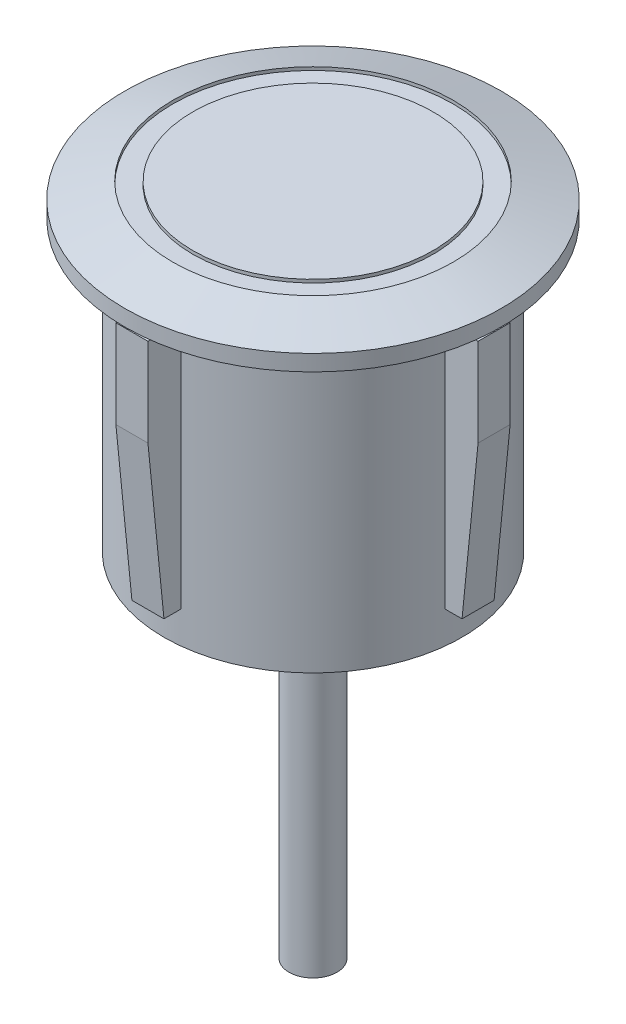
SolidWorks part; units mm, degrees
ref_plane "前视基准面" through (0, 0, 0) normal (0, 0, 1) x (1, 0, 0)
ref_plane "上视基准面" through (0, 0, 0) normal (0, 1, 0) x (1, 0, 0)
ref_plane "右视基准面" through (0, 0, 0) normal (1, 0, 0) x (0, 0, -1)
sketch "草图1" plane through (0, 0, 0) normal (0, 1, 0) x (1, 0, 0)
  circle A0 centre (0, 0) radius 9.3
  dimension "D1" = 18.6
extrude "凸台-拉伸1" add sketch "草图1" along normal blind 20
sketch "草图2" plane through (0, 20, 0) normal (0, 1, 0) x (1, 0, 0)
  circle A0 centre (0, 0) radius 11.75
  dimension "D1" = 23.5
extrude "凸台-拉伸2" add sketch "草图2" against normal blind 2
chamfer "倒角1" distance 1 distance2 3 1 edges at (0, 20, 11.75)
sketch "草图3" plane through (0, 0, 0) normal (0, -1, 0) x (1, 0, 0)
  circle A0 centre (0, 0) radius 1.5
  dimension "D1" = 3
extrude "凸台-拉伸3" add sketch "草图3" along normal blind 22
sketch "草图4" plane through (0, 0, 0) normal (0, -1, 0) x (1, 0, 0)
  line L0 (0, 0) -> (6.8393, 0) construction
  line L1 (1, 7.3) -> (-1, 7.3)
  line L2 (1, 7.3) -> (1, 11.3)
  line L3 (1, 11.3) -> (-1, 11.3)
  line L4 (-1, 7.3) -> (-1, 11.3)
  line L5 (1, 7.3) -> (-1, 11.3) construction
  line L6 (1, 11.3) -> (-1, 7.3) construction
  line L7 (1, -11.3) -> (-1, -7.3) construction
  line L8 (1, -7.3) -> (-1, -11.3) construction
  line L9 (-1, -7.3) -> (-1, -11.3)
  line L10 (1, -11.3) -> (-1, -11.3)
  line L11 (1, -7.3) -> (1, -11.3)
  line L12 (1, -7.3) -> (-1, -7.3)
  line L13 (0, 0) -> (0, 3.0699) construction
  line L14 (0, 0) -> (4.3066, 4.3066) construction
  line L15 (-7.3, 1) -> (-11.3, -1) construction
  line L16 (-11.3, 1) -> (-7.3, -1) construction
  line L17 (-7.3, 1) -> (-7.3, -1)
  line L18 (-7.3, 1) -> (-11.3, 1)
  line L19 (-11.3, 1) -> (-11.3, -1)
  line L20 (-7.3, -1) -> (-11.3, -1)
  line L21 (11.3, 1) -> (7.3, -1) construction
  line L22 (7.3, 1) -> (11.3, -1) construction
  line L23 (7.3, -1) -> (11.3, -1)
  line L24 (11.3, 1) -> (11.3, -1)
  line L25 (7.3, 1) -> (11.3, 1)
  line L26 (7.3, 1) -> (7.3, -1)
  circle A0 centre (0, 0) radius 9.3 construction
  circle A1 centre (0, 0) radius 9.3 construction
  point P0 (0, 9.3)
  point P16 (0, -9.3)
  point P23 (-9.3, 0)
  point P28 (9.3, 0)
  dimension "D1" = 4
  dimension "D2" = 2
  dimension "D3" = 45
extrude "凸台-拉伸4" add sketch "草图4" against normal blind 15.5 from offset 2 offset against normal yes
chamfer "倒角2" distance 10 distance2 1 4 edges at (-11.3, 2, 0) (0, 2, -11.3) (11.3, 2, 0) (0, 2, 11.3)
sketch "草图5" plane through (0, 20, 0) normal (0, 1, 0) x (1, 0, 0)
  circle A0 centre (0, 0) radius 7.5
  circle A1 centre (0, 0) radius 8.75 construction
  circle A2 centre (0, 0) radius 8.75
  dimension "D1" = 15
extrude "切除-拉伸1" cut sketch "草图5" against normal blind 0.2
